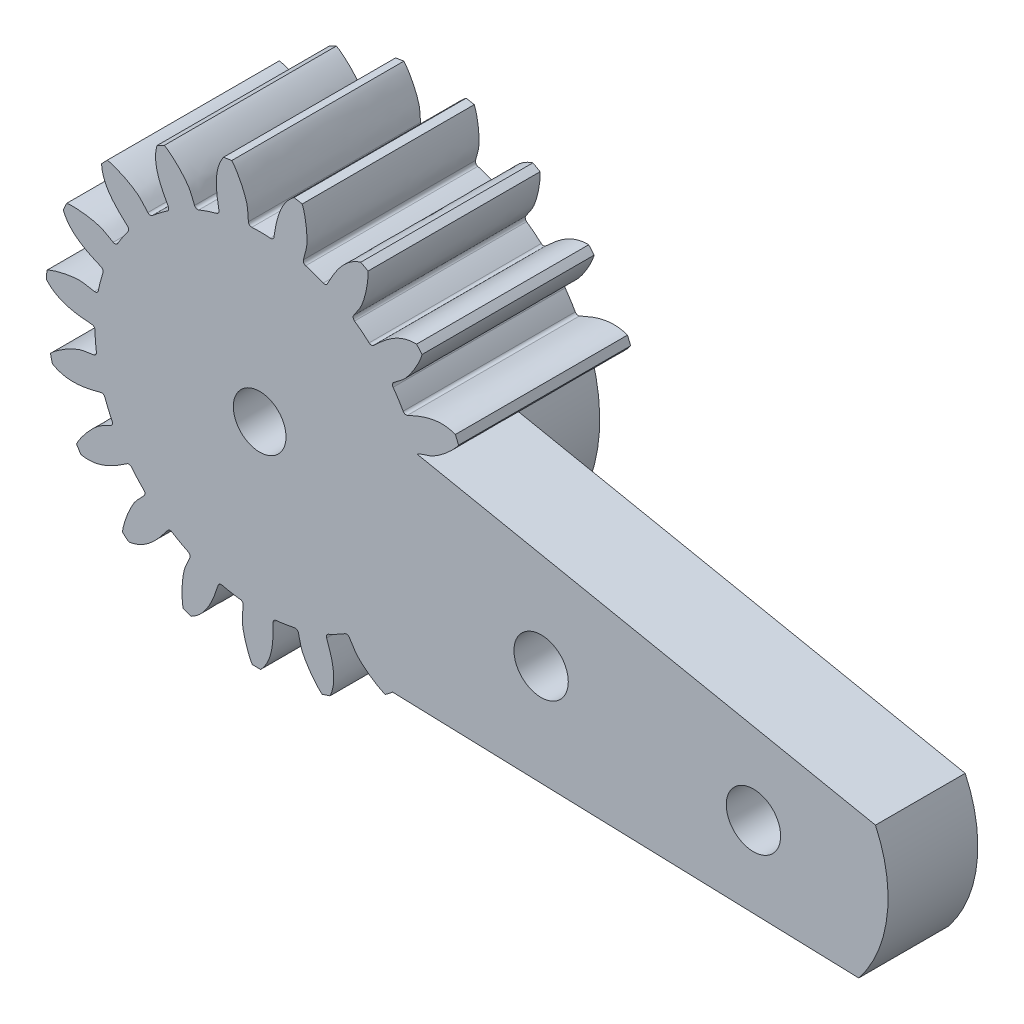
SolidWorks part; units mm, degrees
ref_plane "前视基准面" through (0, 0, 0) normal (0, 0, 1) x (1, 0, 0)
ref_plane "上视基准面" through (0, 0, 0) normal (0, 1, 0) x (1, 0, 0)
ref_plane "右视基准面" through (0, 0, 0) normal (1, 0, 0) x (0, 0, -1)
other "Configuration Table"
sketch "草图3" plane through (0, 0, 0) normal (0, 0, 1) x (1, 0, 0)
  circle A0 centre (0, 0) radius 13
  circle A1 centre (0, 0) radius 10
  dimension "D1" = 26
  dimension "D2" = 20
extrude "凸台-拉伸1" add sketch "草图3" along normal blind 4 contours A1 | A0 A1
sketch "草图6" plane through (0, 0, 4) normal (0, 0, 1) x (1, 0, 0)
  line L0 (0, 14.519) -> (0, -0.3622) construction
  line L5 (0, 0) -> (-1.6968, 12.8888) construction
  line L6 (-1.6968, 12.8888) -> (-1.8736, 14.2316)
  line L7 (-1.8736, 14.2316) -> (3.0009, 14.404)
  line L8 (3.0009, 14.404) -> (2.085, 12.8317)
  arc A0 (0.6559, 9.9785) -> (-0.4764, 9.9886) centre (0, 0) ccw
  circle A1 centre (0, 0) radius 13 construction
  arc A2 (0.6559, 9.9785) -> (0.8668, 10.1484) centre (0.669, 10.178) ccw
  arc A3 (-0.6854, 10.1744) -> (-0.4764, 9.9886) centre (-0.4859, 10.1884) ccw
  spline S0 degree 3 poles (-1.6968, 12.8888) (-1.3404, 12.4914) (-0.7219, 11.2236) (-0.7215, 10.6885) (-0.6854, 10.1744) knots 0 0 0 0 0.644244 0.940775 0.940775 0.940775 0.940775
  spline S1 degree 3 poles (2.085, 12.8317) (1.4718, 12.3854) (1.0735, 11.4242) (0.9081, 10.424) (0.8668, 10.1484) knots 0 0 0 0 0.67612 0.940775 0.940775 0.940775 0.940775
  dimension "D1" = 20
  dimension "D2" = 0.2
  dimension "D3" = 7.5
extrude "切除-拉伸2" cut sketch "草图6" against normal through all both
pattern_circular "阵列(圆周)4" count 19 every 18.947 about axis through (0, 0, 4) along (0, 0, 1) of "切除-拉伸2"
sketch "草图7" plane through (0, 0, 4) normal (0, 0, 1) x (1, 0, 0)
  circle A0 centre (0, 0) radius 12.5
  dimension "D1" = 25
ref_plane "基准面3" through (0, 0, 2) normal (0, 0, 1) x (1, 0, 0)
sketch "草图8" plane through (0, 0, 0) normal (0, 0, -1) x (-1, 0, 0)
  circle A5 centre (0, 0) radius 4.05
  dimension "D1" = 8.1
extrude "切除-拉伸4" cut sketch "草图8" against normal through all both
sketch "草图9" plane through (0, 0, 4) normal (0, 0, 1) x (1, 0, 0)
  line L8 (-1.8658, 22.9242) -> (0, 0) construction
  line L9 (37.3913, -2.5158) -> (9.4988, 3.0887)
  line L13 (0.8103, -9.9555) -> (57.3874, -11.7185)
  line L15 (-0.9329, 11.4621) -> (100.4696, 19.7151) construction
  line L16 (100.1482, 19.1873) -> (20.1614, 12.6773) construction
  line L17 (86.097, 18.0437) -> (83.1063, 17.8003)
  line L18 (0, 0) -> (20.4337, 1.6631) construction
  line L23 (0, 0) -> (1.9441, -23.887) construction
  line L26 (33.2811, 13.7451) -> (30.2904, 13.5017)
  arc A20 (0.8103, -9.9555) -> (9.4988, 3.0887) centre (0, 0) ccw
  arc A21 (33.2811, 13.7451) -> (83.1063, 17.8003) centre (58.1531, 16.271) ccw
  arc A22 (57.3874, -11.7185) -> (86.097, 18.0437) centre (58.1531, 16.271) ccw
  arc A23 (30.2904, 13.5017) -> (37.3913, -2.5158) centre (58.1531, 16.271) ccw
  dimension "D1" = 50
  dimension "D3" = 56
  dimension "D2" = 0.5
sketch "草图10" plane through (0, 0, 0) normal (0, 0, -1) x (-1, 0, 0)
  circle A0 centre (0, 0) radius 4.5
  dimension "D1" = 9
extrude "切除-拉伸5" cut sketch "草图10" against normal blind 0.6
sketch "草图11" plane through (0, 0, 4) normal (0, 0, 1) x (1, 0, 0)
  circle A0 centre (0, 0) radius 4.5
  dimension "D1" = 9
extrude "切除-拉伸6" cut sketch "草图11" against normal blind 0.6
sketch "草图15" plane through (0, 0, 4) normal (0, 0, 1) x (1, 0, 0)
  arc A62 (10.6318, -7.4809) -> (10.9134, -7.0638) centre (0, 0) ccw
  arc A64 (9.6948, 3.1621) -> (9.566, 2.9139) centre (9.7574, 2.9722) ccw
  arc A65 (12.0778, 4.8089) -> (11.8827, 5.2728) centre (0, 0) ccw
  arc A66 (8.7124, 4.9086) -> (8.97, 4.825) centre (8.8866, 5.0068) ccw
  arc A67 (8.7124, 4.9086) -> (8.1016, 5.8621) centre (0, 0) ccw
  arc A68 (8.1428, 6.1387) -> (8.1016, 5.8621) centre (8.2636, 5.9793) ccw
  arc A69 (9.862, 8.47) -> (9.5268, 8.8454) centre (0, 0) ccw
  arc A70 (6.6465, 7.4716) -> (6.9173, 7.4761) centre (6.7794, 7.621) ccw
  arc A71 (6.6465, 7.4716) -> (5.7592, 8.1751) centre (0, 0) ccw
  arc A72 (5.7084, 8.4501) -> (5.7592, 8.1751) centre (5.8744, 8.3386) ccw
  arc A73 (6.5774, 11.2133) -> (6.1385, 11.4595) centre (0, 0) ccw
  arc A74 (3.8603, 9.2248) -> (4.115, 9.3171) centre (3.9375, 9.4093) ccw
  arc A75 (3.8603, 9.2248) -> (2.7927, 9.6021) centre (0, 0) ccw
  arc A76 (2.6553, 9.8457) -> (2.7927, 9.6021) centre (2.8486, 9.7942) ccw
  arc A77 (2.5801, 12.7414) -> (2.085, 12.8317) centre (0, 0) ccw
  arc A78 (0.6559, 9.9785) -> (0.8668, 10.1484) centre (0.669, 10.178) ccw
  arc A79 (0.6559, 9.9785) -> (-0.4764, 9.9886) centre (0, 0) ccw
  arc A80 (-0.6854, 10.1744) -> (-0.4764, 9.9886) centre (-0.4859, 10.1884) ccw
  arc A81 (-1.6968, 12.8888) -> (-2.1944, 12.8134) centre (0, 0) ccw
  arc A82 (-2.6197, 9.6508) -> (-2.4754, 9.88) centre (-2.6721, 9.8438) ccw
  arc A83 (-2.6197, 9.6508) -> (-3.6939, 9.2927) centre (0, 0) ccw
  arc A84 (-3.9519, 9.4006) -> (-3.6939, 9.2927) centre (-3.7678, 9.4786) ccw
  arc A85 (-5.7899, 11.6395) -> (-6.236, 11.4067) centre (0, 0) ccw
  arc A86 (-5.6113, 8.2773) -> (-5.5493, 8.5409) centre (-5.7236, 8.4428) ccw
  arc A87 (-5.6113, 8.2773) -> (-6.5111, 7.5898) centre (0, 0) ccw
  arc A88 (-6.7902, 7.608) -> (-6.5111, 7.5898) centre (-6.6413, 7.7416) ccw
  arc A89 (-9.2555, 9.1288) -> (-9.6019, 8.7638) centre (0, 0) ccw
  arc A90 (-7.9949, 6.0068) -> (-8.0218, 6.2763) centre (-8.1548, 6.1269) ccw
  arc A91 (-7.9949, 6.0068) -> (-8.6227, 5.0644) centre (0, 0) ccw
  arc A92 (-8.8926, 4.9911) -> (-8.6227, 5.0644) centre (-8.7952, 5.1657) ccw
  arc A93 (-11.7181, 5.629) -> (-11.9272, 5.1712) centre (0, 0) ccw
  arc A94 (-9.5121, 3.0854) -> (-9.6251, 3.3315) centre (-9.7024, 3.1471) ccw
  arc A95 (-9.5121, 3.0854) -> (-9.7999, 1.9902) centre (0, 0) ccw
  arc A96 (-10.0314, 1.8332) -> (-9.7999, 1.9902) centre (-9.9959, 2.03) ccw
  arc A97 (-12.9109, 1.5191) -> (-12.9601, 1.0182) centre (0, 0) ccw
  arc A98 (-9.9985, -0.1704) -> (-10.1853, 0.0258) centre (-10.1985, -0.1738) ccw
  arc A99 (-9.9985, -0.1704) -> (-9.9152, -1.2996) centre (0, 0) ccw
  arc A100 (-10.0831, -1.5233) -> (-9.9152, -1.2996) centre (-10.1135, -1.3256) ccw
  arc A101 (-12.7046, -2.7554) -> (-12.5885, -3.2451) centre (0, 0) ccw
  arc A102 (-9.4015, -3.4077) -> (-9.6418, -3.2828) centre (-9.5895, -3.4758) ccw
  arc A103 (-9.4015, -3.4077) -> (-8.956, -4.4487) centre (0, 0) ccw
  arc A104 (-9.0421, -4.7147) -> (-8.956, -4.4487) centre (-9.1351, -4.5376) ccw
  arc A105 (-11.1216, -6.7313) -> (-10.8527, -7.1567) centre (0, 0) ccw
  arc A106 (-7.7856, -6.2757) -> (-8.0535, -6.2356) centre (-7.9413, -6.4012) ccw
  arc A107 (-7.7856, -6.2757) -> (-7.0262, -7.1156) centre (0, 0) ccw
  arc A108 (-7.0213, -7.3953) -> (-7.0262, -7.1156) centre (-7.1667, -7.2579) ccw
  arc A109 (-8.3333, -9.9777) -> (-7.9409, -10.2928) centre (0, 0) ccw
  arc A110 (-5.326, -8.4636) -> (-5.5924, -8.5127) centre (-5.4326, -8.6329) ccw
  arc A111 (-5.326, -8.4636) -> (-4.3351, -9.0115) centre (0, 0) ccw
  arc A112 (-4.2397, -9.2744) -> (-4.3351, -9.0115) centre (-4.4218, -9.1917) ccw
  arc A113 (-4.6421, -12.143) -> (-4.1686, -12.3135) centre (0, 0) ccw
  arc A114 (-2.2893, -9.7344) -> (-2.5253, -9.8673) centre (-2.3351, -9.9291) ccw
  arc A115 (-2.2893, -9.7344) -> (-1.1742, -9.9308) centre (0, 0) ccw
  arc A116 (-0.9986, -10.1485) -> (-1.1742, -9.9308) centre (-1.1976, -10.1294) ccw
  arc A117 (-0.4477, -12.9923) -> (0.0555, -12.9999) centre (0, 0) ccw
  arc A118 (0.9955, -9.9503) -> (0.8154, -10.1526) centre (1.0154, -10.1493) ccw
  arc A119 (3.7951, -12.4337) -> (4.2735, -12.2775) centre (0, 0) ccw
  arc A120 (7.6267, -10.5277) -> (8.0285, -10.2247) centre (0, 0) ccw
  arc A121 (10.6318, -7.4809) -> (10.9134, -7.0638) centre (0, 0) ccw
  arc A122 (8.8746, -4.6089) -> (8.9454, -4.8703) centre (9.052, -4.7011) ccw
  arc A123 (8.8746, -4.6089) -> (8.9454, -4.8703) centre (9.052, -4.7011) ccw
  arc A126 (9.6948, 3.1621) -> (9.566, 2.9139) centre (9.7574, 2.9722) ccw
  arc A127 (12.0778, 4.8089) -> (11.8827, 5.2728) centre (0, 0) ccw
  arc A128 (8.7124, 4.9086) -> (8.97, 4.825) centre (8.8866, 5.0068) ccw
  arc A129 (8.7124, 4.9086) -> (8.1016, 5.8621) centre (0, 0) ccw
  arc A130 (8.1428, 6.1387) -> (8.1016, 5.8621) centre (8.2636, 5.9793) ccw
  arc A131 (9.862, 8.47) -> (9.5268, 8.8454) centre (0, 0) ccw
  arc A132 (6.6465, 7.4716) -> (6.9173, 7.4761) centre (6.7794, 7.621) ccw
  arc A133 (6.6465, 7.4716) -> (5.7592, 8.1751) centre (0, 0) ccw
  arc A134 (5.7084, 8.4501) -> (5.7592, 8.1751) centre (5.8744, 8.3386) ccw
  arc A135 (6.5774, 11.2133) -> (6.1385, 11.4595) centre (0, 0) ccw
  arc A136 (3.8603, 9.2248) -> (4.115, 9.3171) centre (3.9375, 9.4093) ccw
  arc A137 (3.8603, 9.2248) -> (2.7927, 9.6021) centre (0, 0) ccw
  arc A138 (2.6553, 9.8457) -> (2.7927, 9.6021) centre (2.8486, 9.7942) ccw
  arc A139 (2.5801, 12.7414) -> (2.085, 12.8317) centre (0, 0) ccw
  arc A140 (0.6559, 9.9785) -> (0.8668, 10.1484) centre (0.669, 10.178) ccw
  arc A141 (0.6559, 9.9785) -> (-0.4764, 9.9886) centre (0, 0) ccw
  arc A142 (-0.6854, 10.1744) -> (-0.4764, 9.9886) centre (-0.4859, 10.1884) ccw
  arc A143 (-1.6968, 12.8888) -> (-2.1944, 12.8134) centre (0, 0) ccw
  arc A144 (-2.6197, 9.6508) -> (-2.4754, 9.88) centre (-2.6721, 9.8438) ccw
  arc A145 (-2.6197, 9.6508) -> (-3.6939, 9.2927) centre (0, 0) ccw
  arc A146 (-3.9519, 9.4006) -> (-3.6939, 9.2927) centre (-3.7678, 9.4786) ccw
  arc A147 (-5.7899, 11.6395) -> (-6.236, 11.4067) centre (0, 0) ccw
  arc A148 (-5.6113, 8.2773) -> (-5.5493, 8.5409) centre (-5.7236, 8.4428) ccw
  arc A149 (-5.6113, 8.2773) -> (-6.5111, 7.5898) centre (0, 0) ccw
  arc A150 (-6.7902, 7.608) -> (-6.5111, 7.5898) centre (-6.6413, 7.7416) ccw
  arc A151 (-9.2555, 9.1288) -> (-9.6019, 8.7638) centre (0, 0) ccw
  arc A152 (-7.9949, 6.0068) -> (-8.0218, 6.2763) centre (-8.1548, 6.1269) ccw
  arc A153 (-7.9949, 6.0068) -> (-8.6227, 5.0644) centre (0, 0) ccw
  arc A154 (-8.8926, 4.9911) -> (-8.6227, 5.0644) centre (-8.7952, 5.1657) ccw
  arc A155 (-11.7181, 5.629) -> (-11.9272, 5.1712) centre (0, 0) ccw
  arc A156 (-9.5121, 3.0854) -> (-9.6251, 3.3315) centre (-9.7024, 3.1471) ccw
  arc A157 (-9.5121, 3.0854) -> (-9.7999, 1.9902) centre (0, 0) ccw
  arc A158 (-10.0314, 1.8332) -> (-9.7999, 1.9902) centre (-9.9959, 2.03) ccw
  arc A159 (-12.9109, 1.5191) -> (-12.9601, 1.0182) centre (0, 0) ccw
  arc A160 (-9.9985, -0.1704) -> (-10.1853, 0.0258) centre (-10.1985, -0.1738) ccw
  arc A161 (-9.9985, -0.1704) -> (-9.9152, -1.2996) centre (0, 0) ccw
  arc A162 (-10.0831, -1.5233) -> (-9.9152, -1.2996) centre (-10.1135, -1.3256) ccw
  arc A163 (-12.7046, -2.7554) -> (-12.5885, -3.2451) centre (0, 0) ccw
  arc A164 (-9.4015, -3.4077) -> (-9.6418, -3.2828) centre (-9.5895, -3.4758) ccw
  arc A165 (-9.4015, -3.4077) -> (-8.956, -4.4487) centre (0, 0) ccw
  arc A166 (-9.0421, -4.7147) -> (-8.956, -4.4487) centre (-9.1351, -4.5376) ccw
  arc A167 (-11.1216, -6.7313) -> (-10.8527, -7.1567) centre (0, 0) ccw
  arc A168 (-7.7856, -6.2757) -> (-8.0535, -6.2356) centre (-7.9413, -6.4012) ccw
  arc A169 (-7.7856, -6.2757) -> (-7.0262, -7.1156) centre (0, 0) ccw
  arc A170 (-7.0213, -7.3953) -> (-7.0262, -7.1156) centre (-7.1667, -7.2579) ccw
  arc A171 (-8.3333, -9.9777) -> (-7.9409, -10.2928) centre (0, 0) ccw
  arc A172 (-5.326, -8.4636) -> (-5.5924, -8.5127) centre (-5.4326, -8.6329) ccw
  arc A173 (-5.326, -8.4636) -> (-4.3351, -9.0115) centre (0, 0) ccw
  arc A174 (-4.2397, -9.2744) -> (-4.3351, -9.0115) centre (-4.4218, -9.1917) ccw
  arc A175 (-4.6421, -12.143) -> (-4.1686, -12.3135) centre (0, 0) ccw
  arc A176 (-2.2893, -9.7344) -> (-2.5253, -9.8673) centre (-2.3351, -9.9291) ccw
  arc A177 (-2.2893, -9.7344) -> (-1.1742, -9.9308) centre (0, 0) ccw
  arc A178 (-0.9986, -10.1485) -> (-1.1742, -9.9308) centre (-1.1976, -10.1294) ccw
  arc A179 (-0.4477, -12.9923) -> (0.0555, -12.9999) centre (0, 0) ccw
  arc A180 (0.9955, -9.9503) -> (0.8154, -10.1526) centre (1.0154, -10.1493) ccw
  arc A181 (3.7951, -12.4337) -> (4.2735, -12.2775) centre (0, 0) ccw
  arc A182 (7.6267, -10.5277) -> (8.0285, -10.2247) centre (0, 0) ccw
  arc A199 (8.8746, -4.6089) -> (9.3387, -3.5761) centre (0, 0) ccw
  arc A200 (8.8746, -4.6089) -> (9.3387, -3.5761) centre (0, 0) ccw
  arc A201 (9.5928, -3.4593) -> (9.3387, -3.5761) centre (9.5255, -3.6476) ccw
  arc A202 (9.5928, -3.4593) -> (9.3387, -3.5761) centre (9.5255, -3.6476) ccw
  arc A203 (12.4848, -3.6234) -> (12.6157, -3.1375) centre (0, 0) ccw
  arc A204 (12.4848, -3.6234) -> (12.6157, -3.1375) centre (0, 0) ccw
  arc A205 (9.8902, -1.4776) -> (10.0421, -1.7019) centre (10.088, -1.5072) ccw
  arc A206 (9.8902, -1.4776) -> (10.0421, -1.7019) centre (10.088, -1.5072) ccw
  arc A207 (9.8902, -1.4776) -> (9.9939, -0.3501) centre (0, 0) ccw
  arc A208 (9.8902, -1.4776) -> (9.9939, -0.3501) centre (0, 0) ccw
  arc A209 (10.1963, -0.1571) -> (9.9939, -0.3501) centre (10.1937, -0.3571) ccw
  arc A210 (10.1963, -0.1571) -> (9.9939, -0.3501) centre (10.1937, -0.3571) ccw
  arc A211 (12.9849, 0.6267) -> (12.9509, 1.1288) centre (0, 0) ccw
  arc A212 (12.9849, 0.6267) -> (12.9509, 1.1288) centre (0, 0) ccw
  arc A213 (9.8341, 1.8138) -> (10.0506, 1.651) centre (10.0308, 1.85) ccw
  arc A214 (9.8341, 1.8138) -> (10.0506, 1.651) centre (10.0308, 1.85) ccw
  arc A215 (9.8341, 1.8138) -> (9.566, 2.9139) centre (0, 0) ccw
  arc A216 (9.8341, 1.8138) -> (9.566, 2.9139) centre (0, 0) ccw
  arc A217 (0.9955, -9.9503) -> (2.114, -9.774) centre (0, 0) ccw
  arc A218 (0.9955, -9.9503) -> (2.114, -9.774) centre (0, 0) ccw
  arc A219 (2.3508, -9.9228) -> (2.114, -9.774) centre (2.1563, -9.9695) ccw
  arc A220 (2.3508, -9.9228) -> (2.114, -9.774) centre (2.1563, -9.9695) ccw
  arc A221 (4.1724, -9.088) -> (4.0678, -9.3378) centre (4.2559, -9.2697) ccw
  arc A222 (4.1724, -9.088) -> (4.0678, -9.3378) centre (4.2559, -9.2697) ccw
  arc A223 (4.1724, -9.088) -> (5.1731, -8.558) centre (0, 0) ccw
  arc A224 (4.1724, -9.088) -> (5.1731, -8.558) centre (0, 0) ccw
  arc A225 (5.4453, -8.6219) -> (5.1731, -8.558) centre (5.2765, -8.7292) ccw
  arc A226 (5.4453, -8.6219) -> (5.1731, -8.558) centre (5.2765, -8.7292) ccw
  arc A227 (6.8972, -7.2408) -> (6.8794, -7.511) centre (7.0351, -7.3856) ccw
  arc A228 (6.8972, -7.2408) -> (6.8794, -7.511) centre (7.0351, -7.3856) ccw
  arc A229 (6.8972, -7.2408) -> (7.6715, -6.4146) centre (0, 0) ccw
  arc A230 (6.8972, -7.2408) -> (7.6715, -6.4146) centre (0, 0) ccw
  arc A231 (7.9498, -6.3867) -> (7.6715, -6.4146) centre (7.825, -6.5429) ccw
  arc A232 (7.9498, -6.3867) -> (7.6715, -6.4146) centre (7.825, -6.5429) ccw
  spline S31 degree 3 poles (-1783.7839, -881.8485) (18.9669, 21.494) (-14.3831, -33.7039) (72.3219, 78.5696) (-1606.9792, -1169.1861) knots -4.705235 -4.705235 -4.705235 -4.705235 0.296531 9.087902 9.087902 9.087902 9.087902 only from (9.6948, 3.1621) to (12.0778, 4.8089)
  spline S32 degree 3 poles (-372.2799, -1957.0849) (51.7462, -23.6864) (-9.507, 46.1833) (1.9262, -49.9961) (52.3177, 2004.2632) knots -11.806964 -11.806964 -11.806964 -11.806964 0.67612 14.264014 14.264014 14.264014 14.264014 only from (11.8827, 5.2728) to (8.97, 4.825)
  spline S33 degree 3 poles (-1400.7978, -1413.2612) (10.9601, 26.4879) (-2.6601, -36.5479) (42.8918, 97.7954) (-1140.2745, -1627.6217) knots -4.705235 -4.705235 -4.705235 -4.705235 0.296531 9.087902 9.087902 9.087902 9.087902 only from (8.1428, 6.1387) to (9.862, 8.47)
  spline S34 degree 3 poles (283.3557, -1971.9237) (56.6334, -5.601) (-23.9876, 40.594) (18.0555, -46.6618) (-601.3002, 1912.6542) knots -11.806964 -11.806964 -11.806964 -11.806964 0.67612 14.264014 14.264014 14.264014 14.264014 only from (9.5268, 8.8454) to (6.9173, 7.4761)
  spline S35 degree 3 poles (-866.0135, -1791.5251) (1.7656, 28.6115) (9.3511, -35.4314) (8.8137, 106.4235) (-550.0034, -1909.6792) knots -4.705235 -4.705235 -4.705235 -4.705235 0.296531 9.087902 9.087902 9.087902 9.087902 only from (5.7084, 8.4501) to (6.5774, 11.2133)
  spline S36 degree 3 poles (908.2853, -1773.074) (55.3835, 13.0913) (-35.8687, 30.6058) (32.2283, -38.2709) (-1189.7579, 1613.7795) knots -11.806964 -11.806964 -11.806964 -11.806964 0.67612 14.264014 14.264014 14.264014 14.264014 only from (6.1385, 11.4595) to (4.115, 9.3171)
  spline S37 degree 3 poles (-237.3833, -1975.6495) (-7.6202, 27.6345) (20.349, -30.4753) (-26.2195, 103.519) (99.8691, -1984.7933) knots -4.705235 -4.705235 -4.705235 -4.705235 0.296531 9.087902 9.087902 9.087902 9.087902 only from (2.6553, 9.8457) to (2.5801, 12.7414)
  spline S38 degree 3 poles (1434.7881, -1382.0843) (48.1319, 30.3649) (-43.8629, 17.3009) (42.9086, -25.7327) (-1649.2869, 1140.0267) knots -11.806964 -11.806964 -11.806964 -11.806964 0.67612 14.264014 14.264014 14.264014 14.264014 only from (2.085, 12.8317) to (0.8668, 10.1484)
  spline S39 degree 3 poles (416.9711, -1945.6816) (-16.1802, 23.6629) (29.1418, -22.2168) (-58.4114, 89.3966) (738.9193, -1844.8243) knots -4.705235 -4.705235 -4.705235 -4.705235 0.296531 9.087902 9.087902 9.087902 9.087902 only from (-0.6854, 10.1744) to (-1.6968, 12.8888)
  spline S40 degree 3 poles (1805.8093, -841.3242) (35.6645, 44.3481) (-47.1039, 2.1212) (48.9391, -10.4061) (-1930.0901, 542.7343) knots -11.806964 -11.806964 -11.806964 -11.806964 0.67612 14.264014 14.264014 14.264014 14.264014 only from (-2.1944, 12.8134) to (-2.4754, 9.88)
  spline S41 degree 3 poles (1026.1402, -1704.8689) (-22.9869, 17.1271) (34.7766, -11.5507) (-84.2736, 65.5867) (1297.8961, -1504.9399) knots -4.705235 -4.705235 -4.705235 -4.705235 0.296531 9.087902 9.087902 9.087902 9.087902 only from (-3.9519, 9.4006) to (-5.7899, 11.6395)
  spline S42 degree 3 poles (1981.1431, -209.3936) (19.3323, 53.5254) (-45.2404, -13.2883) (49.6663, 6.0482) (-2001.738, -113.3717) knots -11.806964 -11.806964 -11.806964 -11.806964 0.67612 14.264014 14.264014 14.264014 14.264014 only from (-6.236, 11.4067) to (-5.5493, 8.5409)
  spline S43 degree 3 poles (1524.1111, -1279.3072) (-27.3026, 8.7353) (36.6428, 0.3671) (-101.0033, 34.6694) (1716.2257, -1001.972) knots -4.705235 -4.705235 -4.705235 -4.705235 0.296531 9.087902 9.087902 9.087902 9.087902 only from (-6.7902, 7.608) to (-9.2555, 9.1288)
  spline S44 degree 3 poles (1941.7893, 445.228) (0.9051, 56.9025) (-38.4745, -27.2579) (45.0114, 21.8472) (-1856.4666, -757.1922) knots -11.806964 -11.806964 -11.806964 -11.806964 0.67612 14.264014 14.264014 14.264014 14.264014 only from (-9.6019, 8.7638) to (-8.0218, 6.2763)
  spline S45 degree 3 poles (1856.921, -715.1127) (-28.6596, -0.6031) (34.5382, 12.2451) (-106.7879, -0.0048) (1948.5756, -390.4248) knots -4.705235 -4.705235 -4.705235 -4.705235 0.296531 9.087902 9.087902 9.087902 9.087902 only from (-8.8926, 4.9911) to (-11.7181, 5.629)
  spline S46 degree 3 poles (1692.0125, 1051.6023) (-17.6201, 54.1132) (-27.5392, -38.2736) (35.4788, 35.2786) (-1510.0182, -1318.9592) knots -11.806964 -11.806964 -11.806964 -11.806964 0.67612 14.264014 14.264014 14.264014 14.264014 only from (-11.9272, 5.1712) to (-9.6251, 3.3315)
  spline S47 degree 3 poles (1988.5046, -73.4247) (-26.9109, -9.8762) (28.6908, 22.7962) (-101.0002, -34.6785) (1969.7671, 263.4309) knots -4.705235 -4.705235 -4.705235 -4.705235 0.296531 9.087902 9.087902 9.087902 9.087902 only from (-10.0314, 1.8332) to (-12.9109, 1.5191)
  spline S48 degree 3 poles (1258.8799, 1544.0191) (-34.2359, 45.46) (-13.6196, -45.1418) (22.1015, 44.887) (-999.9359, -1737.7964) knots -11.806964 -11.806964 -11.806964 -11.806964 0.67612 14.264014 14.264014 14.264014 14.264014 only from (-12.9601, 1.0182) to (-10.1853, 0.0258)
  spline S49 degree 3 poles (1904.6029, 576.2201) (-22.246, -18.079) (19.7344, 30.8769) (-84.2677, -65.5942) (1777.5038, 888.7399) knots -4.705235 -4.705235 -4.705235 -4.705235 0.296531 9.087902 9.087902 9.087902 9.087902 only from (-10.0831, -1.5233) to (-12.7046, -2.7554)
  spline S50 degree 3 poles (689.3281, 1869.1176) (-47.1418, 31.8805) (1.7758, -47.1182) (6.3292, 49.6313) (-381.495, -1968.3165) knots -11.806964 -11.806964 -11.806964 -11.806964 0.67612 14.264014 14.264014 14.264014 14.264014 only from (-12.5885, -3.2451) to (-9.6418, -3.2828)
  spline S51 degree 3 poles (1614.3079, 1163.4224) (-15.1704, -24.3227) (8.6394, 35.6116) (-58.4034, -89.4018) (1392.6204, 1417.74) knots -4.705235 -4.705235 -4.705235 -4.705235 0.296531 9.087902 9.087902 9.087902 9.087902 only from (-9.0421, -4.7147) to (-11.1216, -6.7313)
  spline S52 degree 3 poles (45.0769, 1991.6681) (-54.9391, 14.8462) (16.9789, -43.9886) (-10.129, 48.9972) (278.2867, -1985.5389) knots -11.806964 -11.806964 -11.806964 -11.806964 0.67612 14.264014 14.264014 14.264014 14.264014 only from (-10.8527, -7.1567) to (-8.0535, -6.2356)
  spline S53 degree 3 poles (1149.0776, 1624.5499) (-6.4508, -27.9307) (-3.3918, 36.4873) (-26.2102, -103.5214) (856.8249, 1793.1061) knots -4.705235 -4.705235 -4.705235 -4.705235 0.296531 9.087902 9.087902 9.087902 9.087902 only from (-7.0213, -7.3953) to (-8.3333, -9.9777)
  spline S54 degree 3 poles (-604.059, 1898.3905) (-56.7829, -3.7969) (30.342, -36.0921) (-25.4895, 43.0535) (907.9118, -1787.5973) knots -11.806964 -11.806964 -11.806964 -11.806964 0.67612 14.264014 14.264014 14.264014 14.264014 only from (-7.9409, -10.2928) to (-5.5924, -8.5127)
  spline S55 degree 3 poles (559.3269, 1909.6322) (2.9678, -28.5119) (-15.0554, 33.409) (8.8232, -106.4227) (228.1792, 1974.1613) knots -4.705235 -4.705235 -4.705235 -4.705235 0.296531 9.087902 9.087902 9.087902 9.087902 only from (-4.2397, -9.2744) to (-4.6421, -12.143)
  spline S56 degree 3 poles (-1187.7358, 1599.3928) (-52.4733, -22.0285) (40.417, -24.2845) (-38.0879, 32.4443) (1439.1506, -1395.9419) knots -11.806964 -11.806964 -11.806964 -11.806964 0.67612 14.264014 14.264014 14.264014 14.264014 only from (-4.1686, -12.3135) to (-2.5253, -9.8673)
  spline S57 degree 3 poles (-91.0355, 1987.7762) (12.0648, -26.0034) (-25.0876, 26.7103) (42.9006, -97.7916) (-425.1933, 1941.2854) knots -4.705235 -4.705235 -4.705235 -4.705235 0.296531 9.087902 9.087902 9.087902 9.087902 only from (-0.9986, -10.1485) to (-0.4477, -12.9923)
  spline S58 degree 3 poles (-1642.703, 1127.0761) (-42.4775, -37.8731) (46.1123, -9.8454) (-46.5588, 18.3193) (1814.435, -853.0145) knots -11.806964 -11.806964 -11.806964 -11.806964 0.67612 14.264014 14.264014 14.264014 14.264014 only from (0.0555, -12.9999) to (0.8154, -10.1526)
  spline S59 degree 3 poles (-731.5328, 1850.5138) (19.8543, -20.677) (-32.4011, 17.1172) (72.329, -78.5631) (-1032.4895, 1698.0412) knots -4.705235 -4.705235 -4.705235 -4.705235 0.296531 9.087902 9.087902 9.087902 9.087902 only from (2.3508, -9.9228) to (3.7951, -12.4337)
  spline S60 degree 3 poles (-1919.6578, 532.6232) (-27.8786, -49.6134) (46.8106, 5.6607) (-49.9844, 2.209) (1993.0973, -217.6497) knots -11.806964 -11.806964 -11.806964 -11.806964 0.67612 14.264014 14.264014 14.264014 14.264014 only from (4.2735, -12.2775) to (4.0678, -9.3378)
  spline S61 degree 3 poles (-1292.7572, 1512.7195) (25.4924, -13.11) (-36.2034, 5.6691) (93.9194, -50.8212) (-1527.8994, 1270.7879) knots -4.705235 -4.705235 -4.705235 -4.705235 0.296531 9.087902 9.087902 9.087902 9.087902 only from (5.4453, -8.6219) to (7.6267, -10.5277)
  spline S62 degree 3 poles (9.6948, 3.1621) (10.1843, 3.3233) (10.7029, 3.455) (11.7801, 4.3658) (12.0778, 4.8089) knots 0 0 0 0 0.296531 0.940775 0.940775 0.940775 0.940775
  spline S63 degree 3 poles (11.8827, 5.2728) (11.1736, 5.5421) (10.1511, 5.3497) (9.2233, 4.9412) (8.97, 4.825) knots 0 0 0 0 0.67612 0.940775 0.940775 0.940775 0.940775
  spline S64 degree 3 poles (8.1428, 6.1387) (8.5534, 6.45) (9.0012, 6.743) (9.7242, 7.9542) (9.862, 8.47) knots 0 0 0 0 0.296531 0.940775 0.940775 0.940775 0.940775
  spline S65 degree 3 poles (9.5268, 8.8454) (8.7687, 8.8699) (7.8641, 8.3559) (7.1192, 7.6683) (6.9173, 7.4761) knots 0 0 0 0 0.67612 0.940775 0.940775 0.940775 0.940775
  spline S66 degree 3 poles (5.7084, 8.4501) (5.9956, 8.8778) (6.324, 9.3003) (6.6146, 10.6807) (6.5774, 11.2133) knots 0 0 0 0 0.296531 0.940775 0.940775 0.940775 0.940775
  spline S67 degree 3 poles (6.1385, 11.4595) (5.4135, 11.2365) (4.7248, 10.4567) (4.2436, 9.5644) (4.115, 9.3171) knots 0 0 0 0 0.67612 0.940775 0.940775 0.940775 0.940775
  spline S68 degree 3 poles (2.6553, 9.8457) (2.7881, 10.3436) (2.9615, 10.8498) (2.7882, 12.2498) (2.5801, 12.7414) knots 0 0 0 0 0.296531 0.940775 0.940775 0.940775 0.940775
  spline S69 degree 3 poles (2.085, 12.8317) (1.4718, 12.3854) (1.0735, 11.4242) (0.9081, 10.424) (0.8668, 10.1484) knots 0 0 0 0 0.67612 0.940775 0.940775 0.940775 0.940775
  spline S70 degree 3 poles (-0.6854, 10.1744) (-0.7215, 10.6885) (-0.7219, 11.2236) (-1.3404, 12.4914) (-1.6968, 12.8888) knots 0 0 0 0 0.296531 0.940775 0.940775 0.940775 0.940775
  spline S71 degree 3 poles (-2.1944, 12.8134) (-2.6295, 12.1922) (-2.6941, 11.1538) (-2.5258, 10.1541) (-2.4754, 9.88) knots 0 0 0 0 0.67612 0.940775 0.940775 0.940775 0.940775
  spline S72 degree 3 poles (-3.9519, 9.4006) (-4.1529, 9.8751) (-4.327, 10.3811) (-5.3237, 11.3793) (-5.7899, 11.6395) knots 0 0 0 0 0.296531 0.940775 0.940775 0.940775 0.940775
  spline S73 degree 3 poles (-6.236, 11.4067) (-6.4459, 10.6778) (-6.1697, 9.6747) (-5.6859, 8.7838) (-5.5493, 8.5409) knots 0 0 0 0 0.67612 0.940775 0.940775 0.940775 0.940775
  spline S74 degree 3 poles (-6.7902, 7.608) (-7.1343, 7.9916) (-7.4633, 8.4136) (-8.7301, 9.0342) (-9.2555, 9.1288) knots 0 0 0 0 0.296531 0.940775 0.940775 0.940775 0.940775
  spline S75 degree 3 poles (-9.6019, 8.7638) (-9.5637, 8.0063) (-8.9768, 7.1472) (-8.23, 6.4616) (-8.0218, 6.2763) knots 0 0 0 0 0.67612 0.940775 0.940775 0.940775 0.940775
  spline S76 degree 3 poles (-8.8926, 4.9911) (-9.3426, 5.242) (-9.7908, 5.5344) (-11.1905, 5.71) (-11.7181, 5.629) knots 0 0 0 0 0.296531 0.940775 0.940775 0.940775 0.940775
  spline S77 degree 3 poles (-11.9272, 5.1712) (-11.6451, 4.4672) (-10.8111, 3.8452) (-9.8821, 3.4392) (-9.6251, 3.3315) knots 0 0 0 0 0.67612 0.940775 0.940775 0.940775 0.940775
  spline S78 degree 3 poles (-10.0314, 1.8332) (-10.5385, 1.9245) (-11.0573, 2.0555) (-12.4382, 1.7671) (-12.9109, 1.5191) knots 0 0 0 0 0.296531 0.940775 0.940775 0.940775 0.940775
  spline S79 degree 3 poles (-12.9601, 1.0182) (-12.4646, 0.4439) (-11.4739, 0.1265) (-10.4634, 0.0442) (-10.1853, 0.0258) knots 0 0 0 0 0.67612 0.940775 0.940775 0.940775 0.940775
  spline S80 degree 3 poles (-10.0831, -1.5233) (-10.5924, -1.6017) (-11.1256, -1.6462) (-12.338, -2.3673) (-12.7046, -2.7554) knots 0 0 0 0 0.296531 0.940775 0.940775 0.940775 0.940775
  spline S81 degree 3 poles (-12.5885, -3.2451) (-11.9334, -3.6274) (-10.8932, -3.6059) (-9.9108, -3.3557) (-9.6418, -3.2828) knots 0 0 0 0 0.67612 0.940775 0.940775 0.940775 0.940775
  spline S82 degree 3 poles (-9.0421, -4.7147) (-9.4984, -4.9542) (-9.9883, -5.1695) (-10.9008, -6.2452) (-11.1216, -6.7313) knots 0 0 0 0 0.296531 0.940775 0.940775 0.940775 0.940775
  spline S83 degree 3 poles (-10.8527, -7.1567) (-10.109, -7.3056) (-9.1322, -6.9476) (-8.2842, -6.3919) (-8.0535, -6.2356) knots 0 0 0 0 0.67612 0.940775 0.940775 0.940775 0.940775
  spline S84 degree 3 poles (-7.0213, -7.3953) (-7.3751, -7.7699) (-7.7686, -8.1326) (-8.2824, -9.4463) (-8.3333, -9.9777) knots 0 0 0 0 0.296531 0.940775 0.940775 0.940775 0.940775
  spline S85 degree 3 poles (-7.9409, -10.2928) (-7.1892, -10.1922) (-6.3815, -9.5364) (-5.7599, -8.7354) (-5.5924, -8.5127) knots 0 0 0 0 0.67612 0.940775 0.940775 0.940775 0.940775
  spline S86 degree 3 poles (-4.2397, -9.2744) (-4.4526, -9.7436) (-4.707, -10.2144) (-4.7664, -11.6238) (-4.6421, -12.143) knots 0 0 0 0 0.296531 0.940775 0.940775 0.940775 0.940775
  spline S87 degree 3 poles (-4.1686, -12.3135) (-3.4902, -11.9742) (-2.9393, -11.0917) (-2.6114, -10.1324) (-2.5253, -9.8673) knots 0 0 0 0 0.67612 0.940775 0.940775 0.940775 0.940775
  spline S88 degree 3 poles (-0.9986, -10.1485) (-1.0476, -10.6614) (-1.1353, -11.1893) (-0.7339, -12.5416) (-0.4477, -12.9923) knots 0 0 0 0 0.296531 0.940775 0.940775 0.940775 0.940775
  spline S89 degree 3 poles (0.0555, -12.9999) (0.5869, -12.4587) (0.8215, -11.4451) (0.82, -10.4313) (0.8154, -10.1526) knots 0 0 0 0 0.67612 0.940775 0.940775 0.940775 0.940775
  spline S90 degree 3 poles (2.3508, -9.9228) (2.4709, -10.4239) (2.5593, -10.9517) (3.3781, -12.1004) (3.7951, -12.4337) knots 0 0 0 0 0.296531 0.940775 0.940775 0.940775 0.940775
  spline S91 degree 3 poles (4.2735, -12.2775) (4.6004, -11.5931) (4.4932, -10.5582) (4.1626, -9.5998) (4.0678, -9.3378) knots 0 0 0 0 0.67612 0.940775 0.940775 0.940775 0.940775
  spline S92 degree 3 poles (5.4453, -8.6219) (5.7217, -9.0568) (5.9767, -9.5273) (7.1241, -10.3479) (7.6267, -10.5277) knots 0 0 0 0 0.296531 0.940775 0.940775 0.940775 0.940775
  spline S100 degree 3 poles (-989.2957, -83.3185) (-1.1721, -41.8195) (29.4009, 10.2514) (-30.6479, -8.1015) (980.5736, 220.3024) knots -9.207047 -9.207047 -9.207047 -9.207047 0.67612 11.538096 11.538096 11.538096 11.538096 only from (8.0285, -10.2247) to (6.8794, -7.511)
  spline S101 degree 3 poles (8.0285, -10.2247) (8.1155, -9.4712) (7.678, -8.5272) (7.0542, -7.7281) (6.8794, -7.511) knots 0 0 0 0 0.67612 0.940775 0.940775 0.940775 0.940775
  spline S102 degree 3 poles (-850.5561, 506.4134) (19.9341, -4.5085) (-19.4118, -6.8549) (73.0652, -14.9052) (-920.2791, 357.7386) knots -3.681392 -3.681392 -3.681392 -3.681392 0.296531 7.356012 7.356012 7.356012 7.356012 only from (7.9498, -6.3867) to (10.6318, -7.4809)
  spline S103 degree 3 poles (7.9498, -6.3867) (8.3524, -6.7083) (8.7464, -7.0704) (10.098, -7.474) (10.6318, -7.4809) knots 0 0 0 0 0.296531 0.940775 0.940775 0.940775 0.940775
  spline S104 degree 3 poles (-908.6395, -400.0279) (12.4702, -39.9342) (24.4792, 19.2424) (-26.3567, -17.6139) (855.9114, 526.7576) knots -9.207047 -9.207047 -9.207047 -9.207047 0.67612 11.538096 11.538096 11.538096 11.538096 only from (10.9134, -7.0638) to (8.9454, -4.8703)
  spline S105 degree 3 poles (10.9134, -7.0638) (10.751, -6.323) (10.0308, -5.5722) (9.1813, -5.0189) (8.9454, -4.8703) knots 0 0 0 0 0.67612 0.940775 0.940775 0.940775 0.940775
  spline S106 degree 3 poles (-968.9028, 202.7994) (20.318, 2.2084) (-16.1342, -12.7865) (73.9461, 9.6267) (-986.5734, 39.5412) knots -3.681392 -3.681392 -3.681392 -3.681392 0.296531 7.356012 7.356012 7.356012 7.356012 only from (9.5928, -3.4593) to (12.4848, -3.6234)
  spline S107 degree 3 poles (9.5928, -3.4593) (10.078, -3.6328) (10.5682, -3.8474) (11.9777, -3.7902) (12.4848, -3.6234) knots 0 0 0 0 0.296531 0.940775 0.940775 0.940775 0.940775
  spline S108 degree 3 poles (-729.518, -673.388) (24.7612, -33.7214) (16.9049, 26.1482) (-19.2094, -25.2175) (638.4978, 776.1303) knots -9.207047 -9.207047 -9.207047 -9.207047 0.67612 11.538096 11.538096 11.538096 11.538096 only from (12.6157, -3.1375) to (10.0421, -1.7019)
  spline S109 degree 3 poles (12.6157, -3.1375) (12.2216, -2.4895) (11.2966, -2.0133) (10.3134, -1.7658) (10.0421, -1.7019) knots 0 0 0 0 0.67612 0.940775 0.940775 0.940775 0.940775
  spline S110 degree 3 poles (-982.2538, -122.791) (18.5, 8.6859) (-11.1083, -17.3325) (66.8137, 33.1153) (-945.9571, -282.9411) knots -3.681392 -3.681392 -3.681392 -3.681392 0.296531 7.356012 7.356012 7.356012 7.356012 only from (10.1963, -0.1571) to (12.9849, 0.6267)
  spline S111 degree 3 poles (10.1963, -0.1571) (10.7115, -0.1636) (11.2449, -0.2074) (12.5594, 0.3043) (12.9849, 0.6267) knots 0 0 0 0 0.296531 0.940775 0.940775 0.940775 0.940775
  spline S112 degree 3 poles (-471.342, -873.7761) (34.3689, -23.8543) (7.4986, 30.2204) (-9.9805, -30.0884) (351.8931, 941.3974) knots -9.207047 -9.207047 -9.207047 -9.207047 0.67612 11.538096 11.538096 11.538096 11.538096 only from (12.9509, 1.1288) to (10.0506, 1.651)
  spline S113 degree 3 poles (12.9509, 1.1288) (12.3677, 1.6137) (11.3382, 1.7638) (10.328, 1.6786) (10.0506, 1.651) knots 0 0 0 0 0.67612 0.940775 0.940775 0.940775 0.940775
  dimension "D1" = 0
extrude "凸台-拉伸6" add sketch "草图15" along normal blind 6.45
sketch "草图16" plane through (0, 0, 4) normal (0, 0, -1) x (-1, 0, 0)
  circle A0 centre (0, 0) radius 1.6
  dimension "D1" = 3.2
extrude "切除-拉伸7" cut sketch "草图16" against normal through all both and the other way through all
extrude "凸台-拉伸7" add sketch "草图9" against normal up to surface (4 mm away) up to face at (-4.5, 0, 0)
sketch "草图17" plane through (0, 0, 4) normal (0, 0, 1) x (1, 0, 0)
  line L4 (8.0331, -10.1806) -> (57.3874, -11.7185)
  line L5 (86.097, 18.0437) -> (83.1063, 17.8003)
  line L6 (33.2811, 13.7451) -> (30.2904, 13.5017)
  line L7 (37.3913, -2.5158) -> (9.5839, 3.0716)
  line L8 (8.0331, -10.1806) -> (57.3874, -11.7185)
  line L9 (86.097, 18.0437) -> (83.1063, 17.8003)
  line L10 (33.2811, 13.7451) -> (30.2904, 13.5017)
  line L11 (37.3913, -2.5158) -> (9.5839, 3.0716)
  arc A18 (9.5839, 3.0716) -> (9.566, 2.9139) centre (9.7574, 2.9722) ccw
  arc A19 (9.8341, 1.8138) -> (9.566, 2.9139) centre (0, 0) ccw
  arc A20 (9.8341, 1.8138) -> (10.0506, 1.651) centre (10.0308, 1.85) ccw
  arc A21 (12.9849, 0.6267) -> (12.9509, 1.1288) centre (0, 0) ccw
  arc A22 (10.1963, -0.1571) -> (9.9939, -0.3501) centre (10.1937, -0.3571) ccw
  arc A23 (9.8902, -1.4776) -> (9.9939, -0.3501) centre (0, 0) ccw
  arc A24 (9.8902, -1.4776) -> (10.0421, -1.7019) centre (10.088, -1.5072) ccw
  arc A25 (12.4848, -3.6234) -> (12.6157, -3.1375) centre (0, 0) ccw
  arc A26 (9.5928, -3.4593) -> (9.3387, -3.5761) centre (9.5255, -3.6476) ccw
  arc A27 (8.8746, -4.6089) -> (9.3387, -3.5761) centre (0, 0) ccw
  arc A28 (8.8746, -4.6089) -> (8.9454, -4.8703) centre (9.052, -4.7011) ccw
  arc A29 (10.6318, -7.4809) -> (10.9134, -7.0638) centre (0, 0) ccw
  arc A30 (7.9498, -6.3867) -> (7.6715, -6.4146) centre (7.825, -6.5429) ccw
  arc A31 (6.8972, -7.2408) -> (7.6715, -6.4146) centre (0, 0) ccw
  arc A32 (6.8972, -7.2408) -> (6.8794, -7.511) centre (7.0351, -7.3856) ccw
  arc A33 (57.3874, -11.7185) -> (86.097, 18.0437) centre (58.1531, 16.271) ccw
  arc A34 (33.2811, 13.7451) -> (83.1063, 17.8003) centre (58.1531, 16.271) ccw
  arc A35 (30.2904, 13.5017) -> (37.3913, -2.5158) centre (58.1531, 16.271) ccw
  arc A36 (9.5839, 3.0716) -> (9.566, 2.9139) centre (9.7574, 2.9722) ccw
  arc A37 (9.8341, 1.8138) -> (9.566, 2.9139) centre (0, 0) ccw
  arc A38 (9.8341, 1.8138) -> (10.0506, 1.651) centre (10.0308, 1.85) ccw
  arc A39 (12.9849, 0.6267) -> (12.9509, 1.1288) centre (0, 0) ccw
  arc A40 (10.1963, -0.1571) -> (9.9939, -0.3501) centre (10.1937, -0.3571) ccw
  arc A41 (9.8902, -1.4776) -> (9.9939, -0.3501) centre (0, 0) ccw
  arc A42 (9.8902, -1.4776) -> (10.0421, -1.7019) centre (10.088, -1.5072) ccw
  arc A43 (12.4848, -3.6234) -> (12.6157, -3.1375) centre (0, 0) ccw
  arc A44 (9.5928, -3.4593) -> (9.3387, -3.5761) centre (9.5255, -3.6476) ccw
  arc A45 (8.8746, -4.6089) -> (9.3387, -3.5761) centre (0, 0) ccw
  arc A46 (8.8746, -4.6089) -> (8.9454, -4.8703) centre (9.052, -4.7011) ccw
  arc A47 (10.6318, -7.4809) -> (10.9134, -7.0638) centre (0, 0) ccw
  arc A48 (7.9498, -6.3867) -> (7.6715, -6.4146) centre (7.825, -6.5429) ccw
  arc A49 (6.8972, -7.2408) -> (7.6715, -6.4146) centre (0, 0) ccw
  arc A50 (6.8972, -7.2408) -> (6.8794, -7.511) centre (7.0351, -7.3856) ccw
  arc A51 (57.3874, -11.7185) -> (86.097, 18.0437) centre (58.1531, 16.271) ccw
  arc A52 (33.2811, 13.7451) -> (83.1063, 17.8003) centre (58.1531, 16.271) ccw
  arc A53 (30.2904, 13.5017) -> (37.3913, -2.5158) centre (58.1531, 16.271) ccw
  spline S7 degree 3 poles (1394.1173, 3754.4058) (-19.5406, -76.0393) (3.6761, 73.0217) (50.356, -63.6991) (-2034.2844, -3434.1473) knots -16.762779 -16.762779 -16.762779 -16.762779 0.264655 16.028002 16.028002 16.028002 16.028002 only from (10.0506, 1.651) to (12.9509, 1.1288)
  spline S8 degree 3 poles (-3803.4112, -1195.9726) (135.6858, 78.5672) (-45.9454, -42.8275) (35.63, 22.9475) (-3955.0683, -524.6) knots -10.333326 -10.333326 -10.333326 -10.333326 0.644244 6.934992 6.934992 6.934992 6.934992 only from (12.9849, 0.6267) to (10.1963, -0.1571)
  spline S9 degree 3 poles (2537.6337, 3098.3126) (-43.1718, -65.5745) (27.187, 67.8716) (26.9445, -76.5983) (-3039.1271, -2587.5447) knots -16.762779 -16.762779 -16.762779 -16.762779 0.264655 16.028002 16.028002 16.028002 16.028002 only from (10.0421, -1.7019) to (12.6157, -3.1375)
  spline S10 degree 3 poles (-3985.6636, 103.7941) (153.8447, 30.2531) (-57.362, -25.5885) (41.1505, 10.1351) (-3911.1091, 788.0328) knots -10.333326 -10.333326 -10.333326 -10.333326 0.644244 6.934992 6.934992 6.934992 6.934992 only from (12.4848, -3.6234) to (9.5928, -3.4593)
  spline S11 degree 3 poles (3406.1582, 2106.4692) (-62.1246, -48.0036) (47.7518, 55.3665) (0.6132, -81.1968) (-3714.6332, -1460.5414) knots -16.762779 -16.762779 -16.762779 -16.762779 0.264655 16.028002 16.028002 16.028002 16.028002 only from (8.9454, -4.8703) to (10.9134, -7.0638)
  spline S12 degree 3 poles (-3736.0075, 1392.3131) (155.3321, -21.3394) (-62.5626, -5.5766) (42.2117, -3.7756) (-3443.3206, 2015.2701) knots -10.333326 -10.333326 -10.333326 -10.333326 0.644244 6.934992 6.934992 6.934992 6.934992 only from (10.6318, -7.4809) to (7.9498, -6.3867)
  spline S13 degree 3 poles (3905.5673, 886.3559) (-74.3452, -25.2308) (63.1418, 36.8615) (-25.7844, -76.9962) (-3987.5756, -175.2652) knots -16.762771 -16.762771 -16.762771 -16.762771 0.264655 16.027968 16.027968 16.027968 16.027968 only from (6.8794, -7.511) to (8.0331, -10.1806)
  spline S14 degree 3 poles (10.0506, 1.651) (10.328, 1.6786) (11.3382, 1.7638) (12.3677, 1.6137) (12.9509, 1.1288) knots 0 0 0 0 0.264655 0.940775 0.940775 0.940775 0.940775
  spline S15 degree 3 poles (12.9849, 0.6267) (12.5594, 0.3043) (11.2449, -0.2074) (10.7115, -0.1636) (10.1963, -0.1571) knots 0 0 0 0 0.644244 0.940775 0.940775 0.940775 0.940775
  spline S16 degree 3 poles (10.0421, -1.7019) (10.3134, -1.7658) (11.2966, -2.0133) (12.2216, -2.4895) (12.6157, -3.1375) knots 0 0 0 0 0.264655 0.940775 0.940775 0.940775 0.940775
  spline S17 degree 3 poles (12.4848, -3.6234) (11.9777, -3.7902) (10.5682, -3.8474) (10.078, -3.6328) (9.5928, -3.4593) knots 0 0 0 0 0.644244 0.940775 0.940775 0.940775 0.940775
  spline S18 degree 3 poles (8.9454, -4.8703) (9.1813, -5.0189) (10.0308, -5.5722) (10.751, -6.323) (10.9134, -7.0638) knots 0 0 0 0 0.264655 0.940775 0.940775 0.940775 0.940775
  spline S19 degree 3 poles (10.6318, -7.4809) (10.098, -7.474) (8.7464, -7.0704) (8.3524, -6.7083) (7.9498, -6.3867) knots 0 0 0 0 0.644244 0.940775 0.940775 0.940775 0.940775
  spline S20 degree 3 poles (6.8794, -7.511) (7.0542, -7.7281) (7.6692, -8.516) (8.1031, -9.4447) (8.0331, -10.1806) knots 0 0 0 0 0.264655 0.927556 0.927556 0.927556 0.927556
  dimension "D1" = 0
extrude "凸台-拉伸8" add sketch "草图17" along normal up to surface (6.45 mm away) up to face at (-1.6, 0, 10.45)
sketch "草图18" plane through (0, 0, 10.45) normal (0, 0, 1) x (1, 0, 0)
  line L3 (-1.8658, 22.9242) -> (0, 0) construction
  line L4 (-15.4817, 10.278) -> (47.9865, 15.4436) construction
  circle A2 centre (26.757, 33.6638) radius 1.65 construction
  circle A3 centre (14.3023, 29.9383) radius 1.65 construction
  circle A6 centre (29.9828, -5.9698) radius 1.65
  circle A7 centre (17.0895, -4.3074) radius 1.65
  dimension "D7" = 11.5
extrude "切除-拉伸8" cut sketch "草图18" against normal through all both and the other way through all
sketch "草图19" plane through (0, 0, 10.45) normal (0, 0, 1) x (1, 0, 0)
  line L0 (86.097, 18.0437) -> (83.1063, 17.8003) construction
  line L1 (8.0331, -10.1806) -> (57.3874, -11.7185) construction
  line L2 (33.2811, 13.7451) -> (30.2904, 13.5017) construction
  line L3 (86.097, 18.0437) -> (83.1063, 17.8003)
  line L4 (37.0354, -11.0843) -> (57.3874, -11.7185)
  line L5 (33.2811, 13.7451) -> (30.2904, 13.5017)
  line L6 (35.3239, 0.0592) -> (35.4721, -1.0159)
  line L7 (35.4721, -1.0159) -> (37.3913, -2.5158)
  line L8 (37.0354, -11.0843) -> (36.3756, -11.0637)
  arc A1 (57.3874, -11.7185) -> (86.097, 18.0437) centre (58.1531, 16.271) ccw construction
  arc A2 (30.2904, 13.5017) -> (37.3913, -2.5158) centre (58.1531, 16.271) ccw construction
  arc A3 (33.2811, 13.7451) -> (83.1063, 17.8003) centre (58.1531, 16.271) ccw construction
  arc A4 (57.3874, -11.7185) -> (86.097, 18.0437) centre (58.1531, 16.271) ccw
  arc A5 (30.2904, 13.5017) -> (35.3239, 0.0592) centre (58.1531, 16.271) ccw
  arc A6 (33.2811, 13.7451) -> (83.1063, 17.8003) centre (58.1531, 16.271) ccw
  arc A7 (36.3756, -11.0637) -> (37.3913, -2.5158) centre (29.9828, -5.9698) ccw
extrude "切除-拉伸9" cut sketch "草图19" against normal through all both
sketch "草图20" plane through (0, 0, 0) normal (0, 0, -1) x (-1, 0, 0)
  line L0 (-3.8843, -9.4287) -> (-4.3084, -10.0645)
  line L1 (-4.3084, -10.0645) -> (-6.4012, -10.2022)
  line L2 (-37.6385, -12.2575) -> (-38.6738, -2.7781)
  line L3 (-38.6738, -2.7781) -> (-36.4867, 0.5007)
  line L4 (-36.4867, 0.5007) -> (-9.6948, 3.1621)
  line L5 (-8.2351, -10.3229) -> (-7.6933, -11.1904)
  line L6 (-7.6933, -11.1904) -> (-6.6969, -10.5681)
  line L7 (-6.6969, -10.5681) -> (-6.4012, -10.2022)
  line L8 (-8.2351, -10.3229) -> (-37.6385, -12.2575)
  arc A0 (-9.6948, 3.1621) -> (-3.8843, -9.4287) centre (0, 0) ccw
extrude "切除-拉伸10" cut sketch "草图20" against normal blind 5
